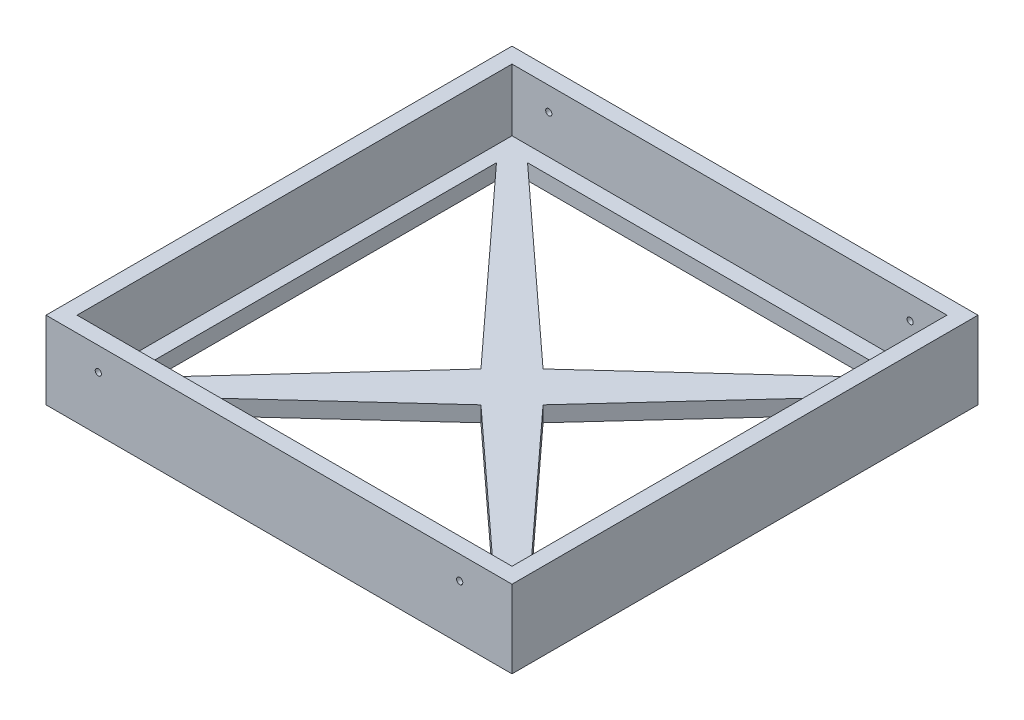
SolidWorks part; units mm, degrees
ref_plane "Front" through (0, 0, 0) normal (0, 0, 1) x (1, 0, 0)
ref_plane "Top" through (0, 0, 0) normal (0, 1, 0) x (1, 0, 0)
ref_plane "Right" through (0, 0, 0) normal (1, 0, 0) x (0, 0, -1)
sketch "Sketch1" plane through (0, 0, 0) normal (0, 1, 0) x (1, 0, 0)
  line L0 (-177.8, 177.8) -> (-177.8, -177.8)
  line L1 (-190.5, 190.5) -> (190.5, 190.5)
  line L2 (-190.5, 190.5) -> (-190.5, -190.5)
  line L3 (-190.5, -190.5) -> (190.5, -190.5)
  line L4 (190.5, 190.5) -> (190.5, -190.5)
  line L5 (-190.5, 190.5) -> (190.5, -190.5) construction
  line L6 (-190.5, -190.5) -> (190.5, 190.5) construction
  line L7 (-177.8, -177.8) -> (177.8, -177.8)
  line L8 (177.8, 177.8) -> (177.8, -177.8)
  line L9 (-177.8, 177.8) -> (177.8, 177.8)
  point P0 (0, 0)
  dimension "D1" = 381
  dimension "D2" = 12.7
extrude "Boss-Extrude2" add sketch "Sketch1" along normal blind 50.8 contours L2 L1 L4 L3 | L0 L7 L8 L9
sketch "Sketch2" plane through (0, 0, -177.8) normal (0, 0, 1) x (1, 0, 0)
  line L4 (-190.5, 0) -> (190.5, 0)
  line L5 (190.5, 0) -> (190.5, 50.8)
  line L6 (190.5, 50.8) -> (-190.5, 50.8)
  line L7 (-190.5, 50.8) -> (-190.5, 0)
  line L8 (-190.5, 0) -> (190.5, 0)
  line L9 (190.5, 0) -> (190.5, 50.8)
  line L10 (190.5, 50.8) -> (-190.5, 50.8)
  line L11 (-190.5, 50.8) -> (-190.5, 0)
  circle A0 centre (-147.7179, 31.75) radius 2.54
  point P4 (0, 0)
  dimension "D2" = 5.08
  dimension "D3" = 19.05
  dimension "D4" = 42.7821
  dimension "D1" = 0
extrude "Cut-Extrude3" cut sketch "Sketch2" against normal through all contours A0
mirror "Mirror1" about plane through (0, 0, 0) normal (0, 0, 1) of "Cut-Extrude3" second plane through (0, 0, 0) second plane normal (1, 0, 0)
sketch "Sketch3" plane through (0, 0, 0) normal (0, -1, 0) x (1, 0, 0)
  line L1 (-190.5, 190.5) -> (190.5, 190.5)
  line L2 (-190.5, 190.5) -> (-190.5, -190.5)
  line L3 (-190.5, -190.5) -> (190.5, -190.5)
  line L4 (190.5, 190.5) -> (190.5, -190.5)
extrude "Boss-Extrude3" add sketch "Sketch3" along normal blind 12.7
sketch "Sketch4" plane through (0, 0, 0) normal (0, 1, 0) x (1, 0, 0)
  line L0 (-152.4, 165.1) -> (0, 25.4)
  line L1 (0, -55) -> (0, 55) construction
  line L2 (152.4, 165.1) -> (0, 25.4)
  line L3 (-177.8, 177.8) -> (-177.8, -177.8) construction
  line L4 (-177.8, 177.8) -> (177.8, 177.8) construction
  line L5 (-152.4, 165.1) -> (152.4, 165.1)
  line L6 (-55, 0) -> (55, 0) construction
  line L7 (165.1, 152.4) -> (165.1, -152.4)
  line L8 (165.1, -152.4) -> (25.4, 0)
  line L9 (165.1, 152.4) -> (25.4, 0)
  line L10 (152.4, -165.1) -> (-152.4, -165.1)
  line L11 (-152.4, -165.1) -> (0, -25.4)
  line L12 (152.4, -165.1) -> (0, -25.4)
  line L13 (-165.1, -152.4) -> (-165.1, 152.4)
  line L14 (-165.1, 152.4) -> (-25.4, 0)
  line L15 (-165.1, -152.4) -> (-25.4, 0)
  point P23 (0, 0)
  dimension "D1" = 25.4
  dimension "D2" = 12.7
  dimension "D3" = 25.4
  dimension "D4" = 4
extrude "Cut-Extrude4" cut sketch "Sketch4" against normal through all contours L13 L14 L15 | L5 L2 L0 | L7 L8 L9 | L10 L11 L12
